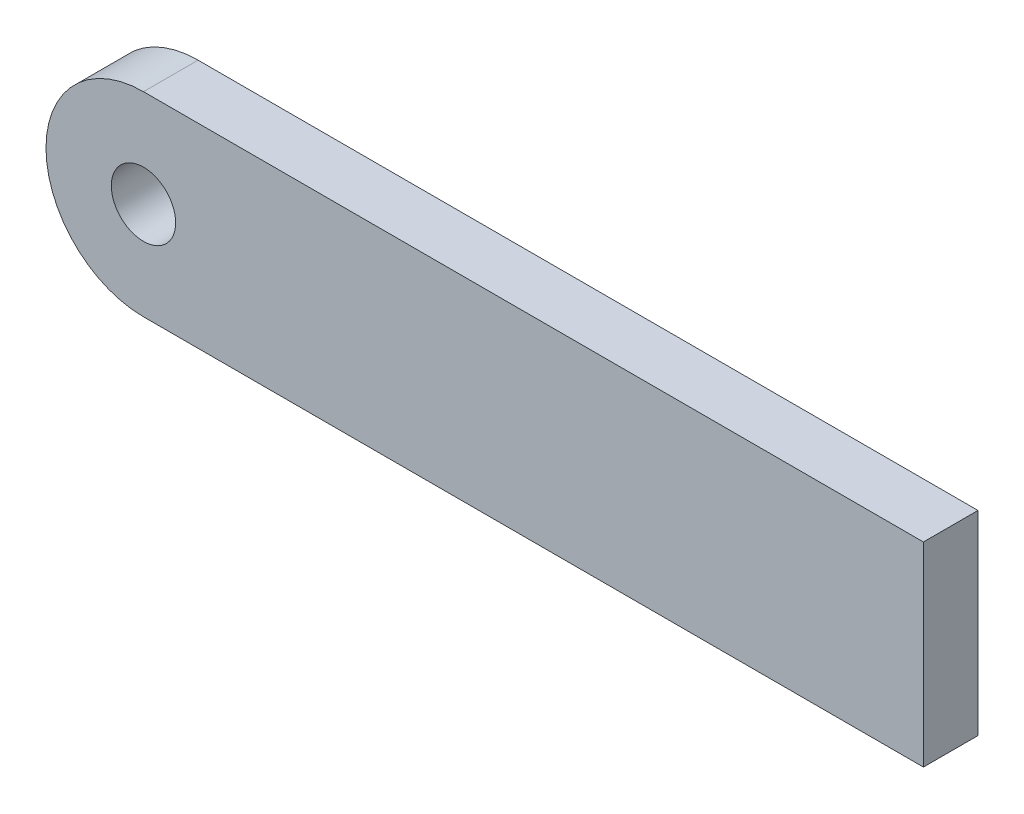
SolidWorks part; units mm, degrees
ref_plane "Plan de face" through (0, 0, 0) normal (0, 0, 1) x (1, 0, 0)
ref_plane "Plan de dessus" through (0, 0, 0) normal (0, 1, 0) x (1, 0, 0)
ref_plane "Plan de droite" through (0, 0, 0) normal (1, 0, 0) x (0, 0, -1)
sketch "Esquisse1" plane through (0, 0, 0) normal (0, 0, 1) x (1, 0, 0)
  line L1 (0, -5) -> (40, -5)
  line L3 (0, 5) -> (40, 5)
  line L4 (40, -5) -> (40, 5)
  arc A0 (0, 5) -> (0, -5) centre (0, 0) ccw
  circle A1 centre (0, 0) radius 1.65
  dimension "D4" = 3.3
  dimension "D1" = 10
  dimension "D2" = 5
  dimension "D3" = 40
extrude "Boss.-Extru.1" add sketch "Esquisse1" along normal mid plane 2.8
